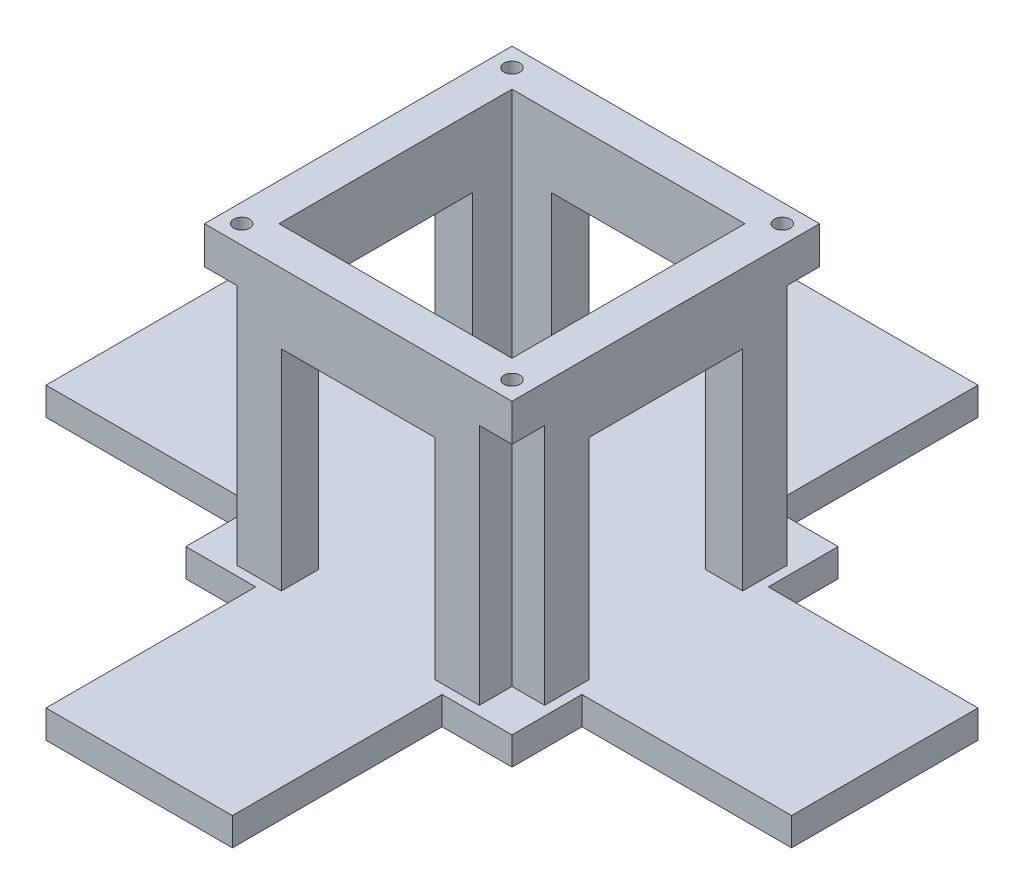
SolidWorks part; units mm, degrees
ref_plane "Front Plane" through (0, 0, 0) normal (0, 0, 1) x (1, 0, 0)
ref_plane "Top Plane" through (0, 0, 0) normal (0, 1, 0) x (1, 0, 0)
ref_plane "Right Plane" through (0, 0, 0) normal (1, 0, 0) x (0, 0, -1)
sketch "Sketch1" plane through (0, 0, 0) normal (0, 1, 0) x (1, 0, 0)
  line L4 (-57.707, 0) -> (67.0064, 0) construction
  line L8 (0, -63.8217) -> (0, 54.8025) construction
  line L24 (-20, 80) -> (20, 80)
  line L25 (-80, 20) -> (-80, -20)
  line L26 (-20, 80) -> (-20, 35)
  line L27 (-20, 35) -> (-35, 35)
  line L28 (-35, 35) -> (-35, 20)
  line L29 (-35, 20) -> (-80, 20)
  line L30 (-35, -20) -> (-80, -20)
  line L31 (-35, -35) -> (-35, -20)
  line L32 (-20, -35) -> (-35, -35)
  line L33 (-20, -80) -> (-20, -35)
  line L34 (-20, -80) -> (20, -80)
  line L35 (20, -80) -> (20, -35)
  line L36 (20, -35) -> (35, -35)
  line L37 (35, -35) -> (35, -20)
  line L38 (35, -20) -> (80, -20)
  line L39 (35, 20) -> (80, 20)
  line L40 (35, 35) -> (35, 20)
  line L41 (20, 35) -> (35, 35)
  line L42 (20, 80) -> (20, 35)
  line L43 (80, 20) -> (80, -20)
  point P9 (-80, 0)
  point P11 (0, 80)
  point P14 (80, 0)
  point P15 (0, -80)
  point P16 (0, 80)
  point P19 (-80, 0)
  point P21 (0, 80)
  point P24 (0, -80)
  point P25 (0, 80)
  point P26 (-80, 0)
  point P28 (0, -80)
  point P37 (0, 80)
  dimension "D1" = 45
  dimension "D2" = 15
  dimension "D3" = 40
extrude "Boss-Extrude1" add sketch "Sketch1" against normal blind 6
sketch "Sketch2" plane through (0, 0, 0) normal (0, 1, 0) x (1, 0, 0)
  line L1 (-33, -33) -> (33, -33)
  line L2 (-33, -33) -> (-33, 33)
  line L3 (-33, 33) -> (33, 33)
  line L4 (33, -33) -> (33, 33)
  line L5 (-33, -33) -> (33, 33) construction
  line L6 (-33, 33) -> (33, -33) construction
  line L7 (-25, -25) -> (25, -25)
  line L8 (-25, -25) -> (-25, 25)
  line L9 (-25, 25) -> (25, 25)
  line L10 (25, -25) -> (25, 25)
  line L11 (-25, -25) -> (25, 25) construction
  line L12 (-25, 25) -> (25, -25) construction
  circle A0 centre (29, 29) radius 1.705
  circle A1 centre (-29, 29) radius 1.705
  circle A2 centre (29, -29) radius 1.705
  circle A3 centre (-29, -29) radius 1.705
  point P0 (0, 0)
  point P6 (0, 0)
  dimension "D1" = 3.41
  dimension "D5" = 4
  dimension "D6" = 4
  dimension "D7" = 4
  dimension "D8" = 4
  dimension "D2" = 8
  dimension "D3" = 50
  dimension "D4" = 50
extrude "Boss-Extrude2" add sketch "Sketch2" along normal blind 60
sketch "Sketch4" plane through (0, 0, 0) normal (0, 1, 0) x (1, 0, 0)
  line L0 (0, -40.6846) -> (0, 40.6846) construction
  line L17 (-33, 33) -> (-26, 33)
  line L18 (-33, 33) -> (-33, 26)
  line L19 (-33, 26) -> (-26, 26)
  line L20 (-26, 33) -> (-26, 26)
  line L21 (26, 33) -> (26, 26)
  line L22 (33, 26) -> (26, 26)
  line L23 (33, 33) -> (33, 26)
  line L24 (33, 33) -> (26, 33)
  line L25 (-43.4188, 0) -> (49.0977, 0) construction
  line L26 (33, -33) -> (26, -33)
  line L27 (33, -33) -> (33, -26)
  line L28 (33, -26) -> (26, -26)
  line L29 (26, -33) -> (26, -26)
  line L30 (-26, -33) -> (-26, -26)
  line L31 (-33, -26) -> (-26, -26)
  line L32 (-33, -33) -> (-33, -26)
  line L33 (-33, -33) -> (-26, -33)
  point P11 (0, 0)
  dimension "D1" = 1
  dimension "D2" = 1
extrude "Cut-Extrude2" cut sketch "Sketch4" along normal blind 52
sketch "Sketch5" plane through (0, 0, 0) normal (0, 1, 0) x (1, 0, 0)
  line L0 (0, -7.0297) -> (0, 37.115) construction
  line L1 (16.5, 33) -> (-16.5, 33)
  line L2 (26, 33) -> (-26, 33) construction
  line L3 (-16.5, 33) -> (-16.5, 25)
  line L4 (25, 25) -> (-25, 25) construction
  line L5 (-16.5, 25) -> (16.5, 25)
  line L6 (16.5, 33) -> (16.5, 25)
  line L7 (-46.8976, 0) -> (51.2236, 0) construction
  line L8 (16.5, -33) -> (16.5, -25)
  line L9 (-16.5, -25) -> (16.5, -25)
  line L10 (-16.5, -33) -> (-16.5, -25)
  line L11 (16.5, -33) -> (-16.5, -33)
  line L12 (25, -16.5) -> (25, 16.5)
  line L13 (25, -25) -> (25, 25) construction
  line L14 (25, -25) -> (25, 25) construction
  line L15 (25, 16.5) -> (33, 16.5)
  line L16 (33, -26) -> (33, 26) construction
  line L17 (33, 16.5) -> (33, -16.5)
  line L18 (25, -16.5) -> (33, -16.5)
  line L19 (-25, -16.5) -> (-33, -16.5)
  line L20 (-33, 16.5) -> (-33, -16.5)
  line L21 (-25, 16.5) -> (-33, 16.5)
  line L22 (-25, -16.5) -> (-25, 16.5)
  point P12 (0, 25)
  point P13 (0, 33)
  point P15 (0, -33)
  point P16 (0, -25)
  point P21 (-25, 0)
  point P32 (33, 0)
  point P33 (25, 0)
  point P34 (-33, 0)
  dimension "D1" = 33
  dimension "D2" = 33
extrude "Cut-Extrude3" cut sketch "Sketch5" along normal blind 45
